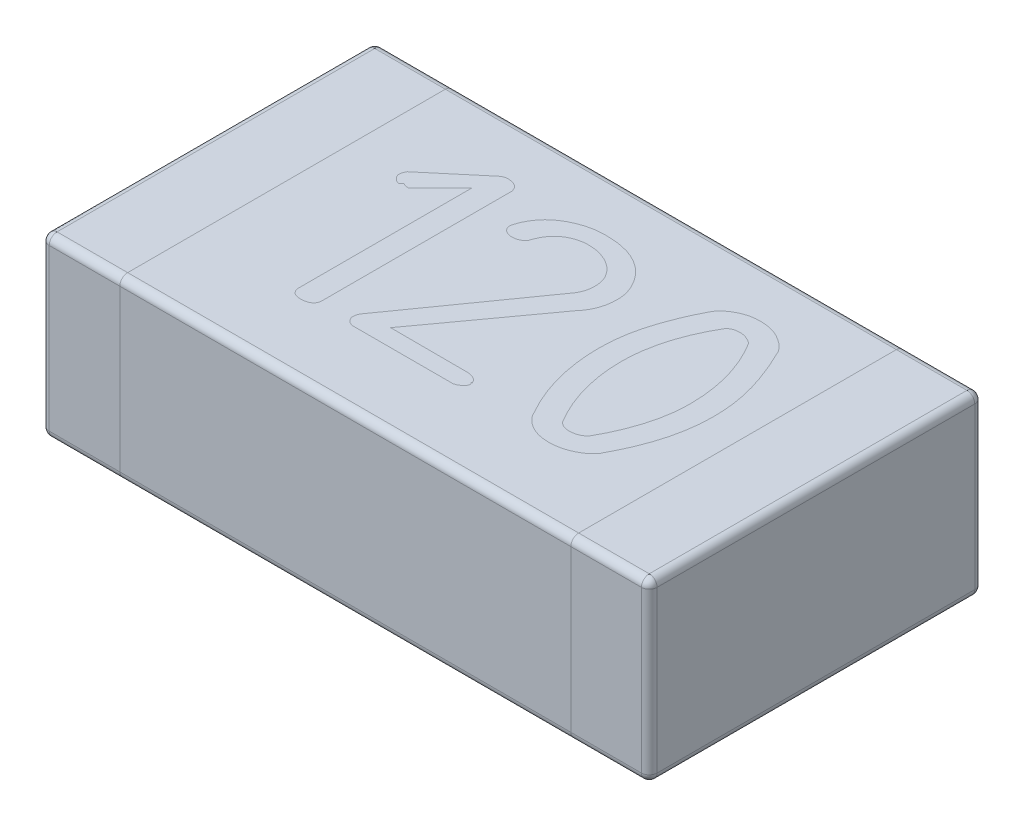
SolidWorks part; units mm, degrees
ref_plane "Front Plane" through (0, 0, 0) normal (0, 0, 1) x (1, 0, 0)
ref_plane "Top Plane" through (0, 0, 0) normal (0, 1, 0) x (1, 0, 0)
ref_plane "Right Plane" through (0, 0, 0) normal (1, 0, 0) x (0, 0, -1)
sketch "Sketch1" plane through (0, 0, 0) normal (0, 1, 0) x (1, 0, 0)
  line L1 (-0.755, -0.425) -> (0.755, -0.425)
  line L2 (-0.775, -0.405) -> (-0.775, 0.405)
  line L3 (-0.755, 0.425) -> (0.755, 0.425)
  line L4 (0.775, -0.405) -> (0.775, 0.405)
  line L5 (-0.775, -0.425) -> (0.775, 0.425) construction
  line L6 (-0.775, 0.425) -> (0.775, -0.425) construction
  arc A4 (-0.775, -0.405) -> (-0.755, -0.425) centre (-0.755, -0.405) ccw
  arc A5 (0.755, -0.425) -> (0.775, -0.405) centre (0.755, -0.405) ccw
  arc A6 (0.775, 0.405) -> (0.755, 0.425) centre (0.755, 0.405) ccw
  arc A7 (-0.755, 0.425) -> (-0.775, 0.405) centre (-0.755, 0.405) ccw
  point P0 (0, 0)
  dimension "D4" = 0.02
  dimension "D1" = 1.55
  dimension "D2" = 0.85
extrude "Boss-Extrude1" add sketch "Sketch1" along normal mid plane 0.45
sketch "Sketch3" plane through (0, 0.225, 0) normal (0, 1, 0) x (1, 0, 0)
  line L0 (-0.575, 0) -> (0.575, 0) construction
  line L1 (-0.575, -0.5133) -> (-0.575, 0.5133)
  line L2 (0.575, -0.5133) -> (0.575, 0.5133)
  line L3 (0, -0.25) -> (0, 0.25) construction
  line L6 (-0.575, -0.25) -> (0.575, -0.25) construction
  text T0 "<b>120</b>\r\n" font "SWIsop1" height 0.53
  point P4 (0, 0)
  point P8 (-0.575, 0)
  point P11 (0.575, 0)
  point P14 (0, 0)
  point P17 (0, -0.25)
  dimension "D1" = 1.15
  dimension "D2" = 0.5
sketch "Sketch4" plane through (0, 0, 0.425) normal (0, 0, 1) x (1, 0, 0)
  line L0 (-0.575, 0.225) -> (-0.575, -0.5946)
  line L1 (0.575, 0.225) -> (0.575, -0.5946)
sketch "Sketch5" plane through (0, 0, -0.425) normal (0, 0, -1) x (-1, 0, 0)
  line L0 (-0.575, 0.225) -> (-0.575, -0.5946) construction
  line L1 (-0.575, 0.225) -> (-0.575, -0.5946)
  line L2 (0.575, 0.225) -> (0.575, -0.5946) construction
  line L3 (0.575, 0.225) -> (0.575, -0.5946)
sketch "Sketch6" plane through (0, -0.225, 0) normal (0, -1, 0) x (1, 0, 0)
  line L0 (0.575, 0.5133) -> (0.575, -0.5133) construction
  line L1 (-0.575, 0.5133) -> (-0.575, -0.5133) construction
  line L2 (0.575, 0.5133) -> (0.575, -0.5133)
  line L3 (-0.575, 0.5133) -> (-0.575, -0.5133)
split line "Split Line2"
split line "Split Line3"
split line "Split Line4"
split line "Split Line5"
fillet "Fillet2" radius 0.02 24 edges at (-0.665, -0.225, 0.425) (0, -0.225, 0.425) (0.665, -0.225, 0.425) (-0.7691, -0.225, 0.4191) (-0.775, -0.225, 0) (-0.7691, -0.225, -0.4191) (0.665, -0.225, -0.425) (0, -0.225, -0.425) (-0.665, -0.225, -0.425) (0.7691, -0.225, -0.4191) (0.775, -0.225, 0) (0.7691, -0.225, 0.4191) (-0.7691, 0.225, 0.4191) (-0.775, 0.225, 0) (-0.7691, 0.225, -0.4191) (0.665, 0.225, -0.425) (0, 0.225, -0.425) (-0.665, 0.225, -0.425) (0.7691, 0.225, -0.4191) (0.775, 0.225, 0) (0.7691, 0.225, 0.4191) (-0.665, 0.225, 0.425) (0, 0.225, 0.425) (0.665, 0.225, 0.425)
